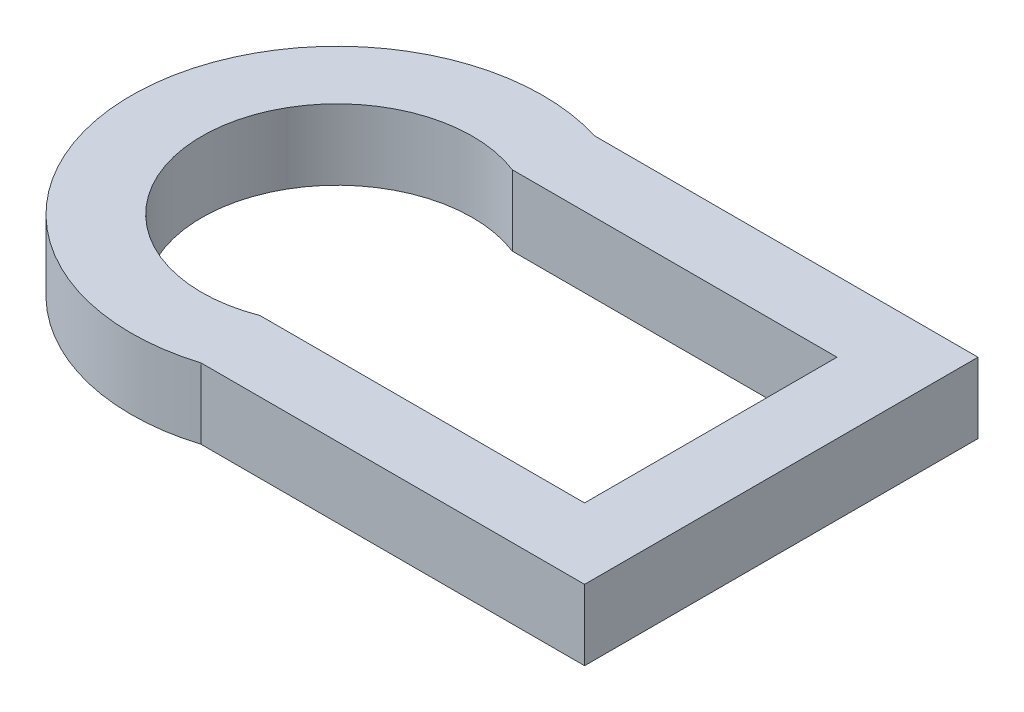
SolidWorks part; units mm, degrees
ref_plane "Front Plane" through (0, 0, 0) normal (0, 0, 1) x (1, 0, 0)
ref_plane "Top Plane" through (0, 0, 0) normal (0, 1, 0) x (1, 0, 0)
ref_plane "Right Plane" through (0, 0, 0) normal (1, 0, 0) x (0, 0, -1)
sketch "Sketch1" plane through (0, 0, 0) normal (0, 1, 0) x (1, 0, 0)
  line L0 (26.5, 0) -> (-9.6, 0) construction
  line L1 (4.3078, -13.95) -> (31.5, -13.95)
  line L2 (3.4724, -8.95) -> (26.5, -8.95)
  line L4 (3.4724, 8.95) -> (26.5, 8.95)
  line L5 (26.5, -8.95) -> (26.5, 8.95)
  line L6 (-0.1582, -8.95) -> (26.5, 8.95) construction
  line L7 (-0.1582, 8.95) -> (26.5, -8.95) construction
  line L8 (31.5, -13.95) -> (31.5, 13.95)
  line L9 (4.3078, 13.95) -> (31.5, 13.95)
  arc A0 (3.4724, 8.95) -> (3.4724, -8.95) centre (0, 0) ccw
  arc A1 (4.3078, 13.95) -> (4.3078, -13.95) centre (0, 0) ccw
  point P4 (13.1709, 0)
  dimension "D1" = 19.2
  dimension "D2" = 17.9
  dimension "D3" = 36.1
  dimension "D4" = 5
extrude "Boss-Extrude1" add sketch "Sketch1" along normal blind 5
